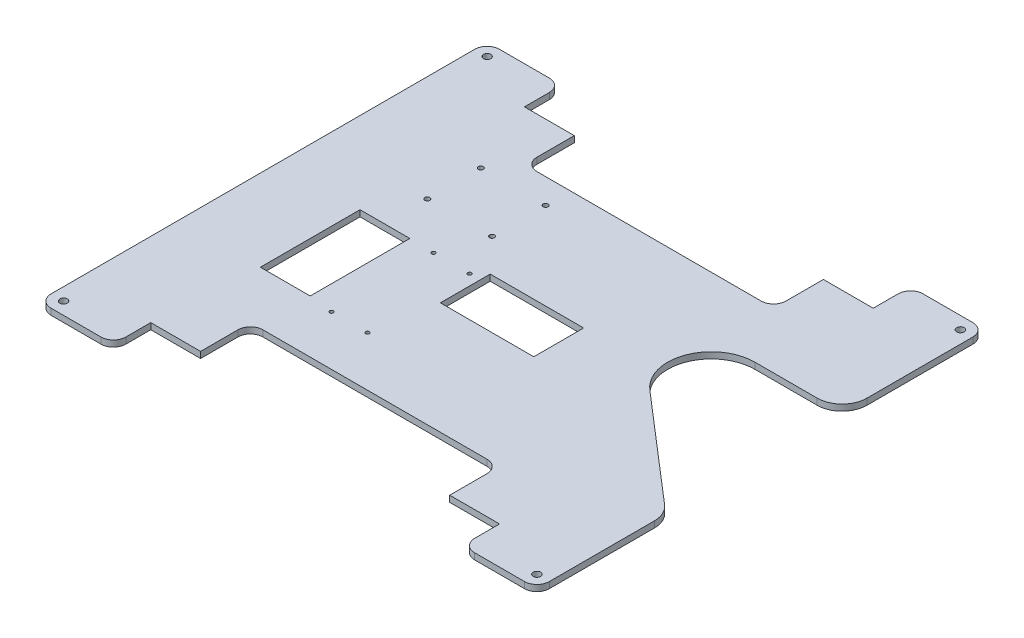
SolidWorks part; units mm, degrees
ref_plane "前基準面" through (0, 0, 0) normal (0, 0, 1) x (1, 0, 0)
ref_plane "上基準面" through (0, 0, 0) normal (0, 1, 0) x (1, 0, 0)
ref_plane "右基準面" through (0, 0, 0) normal (1, 0, 0) x (0, 0, -1)
sketch "草圖4" plane through (0, 0, 0) normal (0, 1, 0) x (1, 0, 0)
  line L0 (-200, 180) -> (-140, 180)
  line L1 (-140, 180) -> (-140, 150)
  line L2 (-140, 150) -> (-100, 150)
  line L3 (-100, 150) -> (-100, 110)
  line L4 (-100, 110) -> (100, 110)
  line L5 (100, 110) -> (100, 150)
  line L6 (100, 150) -> (140, 150)
  line L7 (140, 150) -> (140, 180)
  line L8 (140, 180) -> (200, 180)
  line L9 (-200, 180) -> (-200, -180)
  line L10 (-200, -180) -> (-140, -180)
  line L11 (-140, -180) -> (-140, -150)
  line L12 (-140, -150) -> (-100, -150)
  line L13 (-100, -150) -> (-100, -110)
  line L14 (-100, -110) -> (100, -110)
  line L15 (100, -110) -> (100, -150)
  line L16 (100, -150) -> (140, -150)
  line L17 (140, -150) -> (140, -180)
  line L18 (140, -180) -> (200, -180)
  line L19 (200, -180) -> (200, 180)
  line L20 (-100, 150) -> (100, 150) construction
  line L22 (100, -150) -> (-100, -150) construction
  line L24 (-140, 180) -> (140, 180) construction
  line L25 (140, -180) -> (-140, -180) construction
  line L27 (-100, 110) -> (100, -110) construction
  circle A0 centre (0, 0) radius 15
  dimension "D9" = 30
  dimension "D1" = 40
  dimension "D2" = 60
  dimension "D3" = 200
  dimension "D4" = 30
  dimension "D5" = 70
  dimension "D6" = 360
  dimension "D7" = 60
  dimension "D8" = 40
extrude "伸長1" add sketch "草圖4" along normal blind 5
sketch "草圖6" plane through (0, 5, 0) normal (0, 1, 0) x (-1, 0, 0)
  line L0 (200, -180) -> (200, 180) construction
  line L1 (115, -90) -> (63, -90) construction
  line L2 (115, -90) -> (115, -47) construction
  line L3 (115, -47) -> (63, -47) construction
  line L4 (63, -90) -> (63, -47) construction
  line L5 (115, -90) -> (63, -47) construction
  line L6 (115, -47) -> (63, -90) construction
  line L7 (75, -12) -> (46, -12) construction
  line L8 (75, -12) -> (75, 70) construction
  line L9 (75, 70) -> (46, 70) construction
  line L10 (46, -12) -> (46, 70) construction
  line L11 (75, -12) -> (46, 70) construction
  line L12 (75, 70) -> (46, -12) construction
  line L13 (33, -16.5) -> (-33, -16.5) construction
  line L14 (33, -16.5) -> (33, 16.5) construction
  line L15 (33, 16.5) -> (-33, 16.5) construction
  line L16 (-33, -16.5) -> (-33, 16.5) construction
  line L17 (33, -16.5) -> (-33, 16.5) construction
  line L18 (33, 16.5) -> (-33, -16.5) construction
  line L19 (130, -10) -> (99, -10) construction
  line L20 (130, -10) -> (130, 65) construction
  line L21 (130, 65) -> (99, 65) construction
  line L22 (99, -10) -> (99, 65) construction
  line L23 (130, -10) -> (99, 65) construction
  line L24 (130, 65) -> (99, -10) construction
  line L25 (100, 110) -> (-100, 110) construction
  line L26 (-100, -110) -> (100, -110) construction
  circle A0 centre (75, -12) radius 1.5
  circle A1 centre (46, -12) radius 1.5
  circle A2 centre (46, 70) radius 1.5
  circle A3 centre (75, 70) radius 1.5
  circle A4 centre (63, -90) radius 2
  circle A5 centre (115, -90) radius 2
  circle A6 centre (115, -47) radius 2
  circle A7 centre (63, -47) radius 2
  circle A8 centre (130, -10) radius 1.6
  circle A9 centre (130, 65) radius 1.6
  circle A10 centre (99, 65) radius 1.6
  circle A11 centre (99, -10) radius 1.6
  circle A12 centre (33, 16.5) radius 1.75
  circle A13 centre (33, -16.5) radius 1.75
  circle A14 centre (-33, -16.5) radius 1.75
  circle A15 centre (-33, 16.5) radius 1.75
  point P0 (89, -68.5)
  point P5 (60.5, 29)
  point P10 (0, 0)
  point P15 (114.5, 27.5)
  dimension "D1" = 29
  dimension "D3" = 3
  dimension "D4" = 4
  dimension "D7" = 3.2
  dimension "D10" = 3.5
  dimension "D2" = 82
  dimension "D5" = 52
  dimension "D6" = 43
  dimension "D8" = 31
  dimension "D9" = 75
  dimension "D11" = 66
  dimension "D12" = 33
  dimension "D13" = 70
  dimension "D14" = 125
  dimension "D15" = 85
  dimension "D16" = 45
  dimension "D17" = 40
  dimension "D18" = 20
extrude "伸長2" cut sketch "草圖6" against normal blind 5
sketch "草圖7" plane through (0, 5, 0) normal (0, 1, 0) x (1, 0, 0)
  line L0 (15, -92) -> (-15, -92) construction
  line L1 (15, -102) -> (-15, -102) construction
  line L2 (15, -102) -> (15, -52) construction
  line L3 (15, -52) -> (-15, -52) construction
  line L4 (-15, -102) -> (-15, -52) construction
  line L5 (15, -102) -> (-15, -52) construction
  line L6 (15, -52) -> (-15, -102) construction
  line L7 (-15, -82) -> (15, -82) construction
  line L8 (15, -72) -> (-15, -72) construction
  line L9 (-15, -62) -> (15, -62) construction
  line L10 (15, 62) -> (-15, 62) construction
  line L11 (15, 52) -> (-15, 52) construction
  line L12 (15, 52) -> (15, 102) construction
  line L13 (15, 102) -> (-15, 102) construction
  line L14 (-15, 52) -> (-15, 102) construction
  line L15 (15, 52) -> (-15, 102) construction
  line L16 (15, 102) -> (-15, 52) construction
  line L17 (-15, 72) -> (15, 72) construction
  line L18 (15, 82) -> (-15, 82) construction
  line L19 (-15, 92) -> (15, 92) construction
  line L20 (0, 77) -> (0, -77) construction
  line L21 (-100, -110) -> (100, -110) construction
  circle A0 centre (-15, -102) radius 1.5
  circle A1 centre (-15, -92) radius 1.5
  circle A2 centre (-15, -82) radius 1.5
  circle A3 centre (-15, -72) radius 1.5
  circle A4 centre (-15, -62) radius 1.5
  circle A5 centre (-15, -52) radius 1.5
  circle A6 centre (15, -102) radius 1.5
  circle A7 centre (15, -92) radius 1.5
  circle A8 centre (15, -72) radius 1.5
  circle A9 centre (15, -62) radius 1.5
  circle A10 centre (15, -52) radius 1.5
  circle A11 centre (15, -82) radius 1.5
  circle A12 centre (-15, 52) radius 1.5
  circle A13 centre (-15, 62) radius 1.5
  circle A14 centre (-15, 72) radius 1.5
  circle A15 centre (-15, 82) radius 1.5
  circle A16 centre (-15, 92) radius 1.5
  circle A17 centre (-15, 102) radius 1.5
  circle A18 centre (15, 52) radius 1.5
  circle A19 centre (15, 62) radius 1.5
  circle A20 centre (15, 82) radius 1.5
  circle A21 centre (15, 92) radius 1.5
  circle A22 centre (15, 102) radius 1.5
  circle A23 centre (15, 72) radius 1.5
  point P0 (0, -77)
  point P25 (37.8027, -51.0899)
  point P26 (0, 77)
  dimension "D13" = 3
  dimension "D14" = 3
  dimension "D1" = 10
  dimension "D2" = 10
  dimension "D3" = 10
  dimension "D4" = 10
  dimension "D5" = 10
  dimension "D6" = 30
  dimension "D7" = 50
  dimension "D8" = 30
  dimension "D9" = 10
  dimension "D10" = 10
  dimension "D11" = 10
  dimension "D12" = 10
  dimension "D15" = 8
extrude "伸長3" [suppressed] cut sketch "草圖7" against normal through all
sketch "草圖8" plane through (0, 5, 0) normal (0, 1, 0) x (1, 0, 0)
  line L0 (-140, 180) -> (-200, 180) construction
  line L1 (190, 170) -> (-190, 170) construction
  line L2 (190, 170) -> (190, -170) construction
  line L3 (190, -170) -> (-190, -170) construction
  line L4 (-190, 170) -> (-190, -170) construction
  line L5 (190, 170) -> (-190, -170) construction
  line L6 (190, -170) -> (-190, 170) construction
  line L7 (-200, 180) -> (-200, -180) construction
  circle A0 centre (190, 170) radius 3
  circle A1 centre (-190, 170) radius 3
  circle A2 centre (-190, -170) radius 3
  circle A3 centre (190, -170) radius 3
  point P8 (0, 0)
  dimension "D1" = 6
  dimension "D2" = 10
  dimension "D3" = 10
extrude "伸長4" cut sketch "草圖8" against normal blind 10
sketch "草圖10" plane through (0, 5, 0) normal (0, 1, 0) x (1, 0, 0)
  line L0 (50, 50) -> (95, 50) construction
  line L1 (100, -50) -> (95, -50)
  line L2 (100, -50) -> (100, -25)
  line L3 (100, -25) -> (95, -25)
  line L4 (95, -50) -> (95, -25)
  line L5 (50, -50) -> (45, -50)
  line L6 (50, -50) -> (50, -25)
  line L7 (50, -25) -> (45, -25)
  line L8 (45, -50) -> (45, -25)
  line L9 (100, 25) -> (95, 25)
  line L10 (100, 25) -> (100, 50)
  line L11 (100, 50) -> (95, 50)
  line L12 (95, 25) -> (95, 50)
  line L13 (50, 25) -> (45, 25)
  line L14 (50, 25) -> (50, 50)
  line L15 (50, 50) -> (45, 50)
  line L16 (45, 25) -> (45, 50)
  line L17 (50, -25) -> (95, -25) construction
  line L18 (45, 25) -> (45, -25) construction
  line L19 (95, 25) -> (95, -25) construction
  line L20 (50, 25) -> (95, 25) construction
  line L21 (50, -50) -> (95, -50) construction
  line L22 (50, 25) -> (50, -25) construction
  line L23 (100, 25) -> (100, -25) construction
  line L24 (50, 12.5) -> (95, 12.5) construction
  line L25 (45, 12.5) -> (50, 12.5)
  line L26 (45, 12.5) -> (45, -12.5)
  line L27 (45, -12.5) -> (50, -12.5)
  line L28 (50, 12.5) -> (50, -12.5)
  line L29 (95, 12.5) -> (100, 12.5)
  line L30 (95, 12.5) -> (95, -12.5)
  line L31 (95, -12.5) -> (100, -12.5)
  line L32 (100, 12.5) -> (100, -12.5)
  line L33 (50, -12.5) -> (95, -12.5) construction
  line L34 (50, 12.5) -> (95, -12.5) construction
  line L35 (50, -12.5) -> (95, 12.5) construction
  line L36 (72.5, 0) -> (0, 0) construction
  dimension "D1" = 25
  dimension "D2" = 5
  dimension "D3" = 45
  dimension "D4" = 100
  dimension "D5" = 12.5
  dimension "D6" = 45
extrude "伸長6" [suppressed] cut sketch "草圖10" against normal blind 10
sketch "草圖12" plane through (0, 5, 0) normal (0, 1, 0) x (1, 0, 0)
  line L0 (135, 94.9) -> (135, 85.1) construction
  line L1 (139.5, 100) -> (180, 100)
  line L2 (139.5, 100) -> (139.5, 80)
  line L3 (139.5, 80) -> (180, 80)
  line L4 (180, 100) -> (180, 80)
  line L5 (139.5, 100) -> (180, 80) construction
  line L6 (139.5, 80) -> (180, 100) construction
  line L7 (184.5, 94.9) -> (184.5, 85.1) construction
  line L8 (135, 90) -> (184.5, 90) construction
  line L9 (135, 94.9) -> (184.5, 94.9) construction
  line L10 (135, -85.1) -> (135, -94.9) construction
  line L11 (139.5, -80) -> (180, -80)
  line L12 (139.5, -80) -> (139.5, -100)
  line L13 (139.5, -100) -> (180, -100)
  line L14 (180, -80) -> (180, -100)
  line L15 (139.5, -80) -> (180, -100) construction
  line L16 (139.5, -100) -> (180, -80) construction
  line L17 (184.5, -85.1) -> (184.5, -94.9) construction
  line L18 (135, -90) -> (184.5, -90) construction
  line L19 (135, -85.1) -> (184.5, -85.1) construction
  line L20 (159.75, 90) -> (159.75, -90) construction
  line L21 (0, 0) -> (159.75, 0) construction
  line L22 (200, -180) -> (200, 180) construction
  line L23 (200, 180) -> (140, 180) construction
  circle A0 centre (135, 94.9) radius 2.25
  circle A1 centre (135, 85.1) radius 2.25
  circle A2 centre (184.5, 94.9) radius 2.25
  circle A3 centre (184.5, 85.1) radius 2.25
  circle A4 centre (135, -85.1) radius 2.25
  circle A5 centre (135, -94.9) radius 2.25
  circle A6 centre (184.5, -85.1) radius 2.25
  circle A7 centre (184.5, -94.9) radius 2.25
  point P0 (159.75, 90)
  point P15 (159.75, -90)
  dimension "D1" = 4.5
  dimension "D6" = 4.5
  dimension "D2" = 40.5
  dimension "D3" = 20
  dimension "D4" = 9.8
  dimension "D5" = 4.5
  dimension "D7" = 40.5
  dimension "D8" = 20
  dimension "D9" = 9.8
  dimension "D10" = 4.5
  dimension "D11" = 20
  dimension "D12" = 80
extrude "伸長7" [suppressed] cut sketch "草圖12" against normal blind 10
sketch "草圖13" plane through (0, 5, 0) normal (0, 1, 0) x (-1, 0, 0)
  line L0 (-152.5, -138.75) -> (-180, -138.75) construction
  line L1 (180, -138.75) -> (152.5, -138.75) construction
  line L2 (180, -138.75) -> (180, -111.25) construction
  line L3 (180, -111.25) -> (152.5, -111.25) construction
  line L4 (152.5, -138.75) -> (152.5, -111.25) construction
  line L5 (180, -138.75) -> (152.5, -111.25) construction
  line L6 (180, -111.25) -> (152.5, -138.75) construction
  line L7 (-152.5, -138.75) -> (-152.5, -111.25) construction
  line L8 (-152.5, -111.25) -> (-180, -111.25) construction
  line L9 (-180, -138.75) -> (-180, -111.25) construction
  line L10 (-152.5, -138.75) -> (-180, -111.25) construction
  line L11 (-152.5, -111.25) -> (-180, -138.75) construction
  line L12 (180, 111.25) -> (152.5, 111.25) construction
  line L13 (180, 111.25) -> (180, 138.75) construction
  line L14 (180, 138.75) -> (152.5, 138.75) construction
  line L15 (152.5, 111.25) -> (152.5, 138.75) construction
  line L16 (180, 111.25) -> (152.5, 138.75) construction
  line L17 (180, 138.75) -> (152.5, 111.25) construction
  line L18 (-152.5, 111.25) -> (-180, 111.25) construction
  line L19 (-152.5, 111.25) -> (-152.5, 138.75) construction
  line L20 (-152.5, 138.75) -> (-180, 138.75) construction
  line L21 (-180, 111.25) -> (-180, 138.75) construction
  line L22 (-152.5, 111.25) -> (-180, 138.75) construction
  line L23 (-152.5, 138.75) -> (-180, 111.25) construction
  line L24 (-200, 180) -> (-200, -180) construction
  line L25 (166.25, -125) -> (-166.25, -125) construction
  line L26 (166.25, -125) -> (166.25, 125) construction
  line L27 (166.25, 125) -> (-166.25, 125) construction
  line L28 (-166.25, -125) -> (-166.25, 125) construction
  line L29 (166.25, -125) -> (-166.25, 125) construction
  line L30 (166.25, 125) -> (-166.25, -125) construction
  line L31 (100, -150) -> (140, -150) construction
  circle A0 centre (180, -138.75) radius 2.5
  circle A1 centre (152.5, -138.75) radius 2.5
  circle A2 centre (152.5, -111.25) radius 2.5
  circle A3 centre (180, -111.25) radius 2.5
  circle A4 centre (-152.5, -138.75) radius 2.5
  circle A5 centre (-180, -138.75) radius 2.5
  circle A6 centre (-180, -111.25) radius 2.5
  circle A7 centre (-152.5, -111.25) radius 2.5
  circle A8 centre (180, 111.25) radius 2.5
  circle A9 centre (152.5, 111.25) radius 2.5
  circle A10 centre (152.5, 138.75) radius 2.5
  circle A11 centre (180, 138.75) radius 2.5
  circle A12 centre (-152.5, 111.25) radius 2.5
  circle A13 centre (-180, 111.25) radius 2.5
  circle A14 centre (-180, 138.75) radius 2.5
  circle A15 centre (-152.5, 138.75) radius 2.5
  point P0 (166.25, -125)
  point P9 (-166.25, -125)
  point P18 (166.25, 125)
  point P27 (-166.25, 125)
  point P36 (0, 0)
  dimension "D1" = 5
  dimension "D2" = 27.5
  dimension "D3" = 27.5
  dimension "D4" = 27.5
  dimension "D5" = 27.5
  dimension "D6" = 27.5
  dimension "D7" = 27.5
  dimension "D8" = 27.5
  dimension "D9" = 27.5
  dimension "D10" = 20
  dimension "D11" = 25
extrude "伸長8" [suppressed] cut sketch "草圖13" against normal blind 10
sketch "草圖14" plane through (0, 5, 0) normal (0, 1, 0) x (1, 0, 0)
  line L0 (200, 0) -> (280, 0) construction
  line L1 (200, -180) -> (200, 180) construction
  circle A0 centre (280, 0) radius 100
  dimension "D1" = 200
  dimension "D2" = 80
extrude "伸長9" [suppressed] cut sketch "草圖14" against normal blind 10
sketch "草圖15" plane through (0, 5, 0) normal (0, 1, 0) x (1, 0, 0)
  line L0 (155, 5) -> (165, 5) construction
  line L1 (115, 5) -> (125, 5) construction
  line L2 (115, 5) -> (115, -5) construction
  line L3 (115, -5) -> (125, -5) construction
  line L4 (125, 5) -> (125, -5) construction
  line L5 (115, 5) -> (125, -5) construction
  line L6 (115, -5) -> (125, 5) construction
  line L7 (155, 5) -> (155, -5) construction
  line L8 (155, -5) -> (165, -5) construction
  line L9 (165, 5) -> (165, -5) construction
  line L10 (155, 5) -> (165, -5) construction
  line L11 (155, -5) -> (165, 5) construction
  line L12 (135, 5) -> (145, 5) construction
  line L13 (135, 5) -> (135, -5) construction
  line L14 (135, -5) -> (145, -5) construction
  line L15 (145, 5) -> (145, -5) construction
  line L16 (135, 5) -> (145, -5) construction
  line L17 (135, -5) -> (145, 5) construction
  line L18 (120, 0) -> (140, 0) construction
  line L19 (140, 0) -> (160, 0) construction
  line L20 (120, 0) -> (0, 0) construction
  circle A0 centre (125, 5) radius 1.5
  circle A1 centre (125, -5) radius 1.5
  circle A2 centre (115, 5) radius 1.5
  circle A3 centre (115, -5) radius 1.5
  circle A4 centre (165, 5) radius 1.5
  circle A5 centre (165, -5) radius 1.5
  circle A6 centre (155, 5) radius 1.5
  circle A7 centre (155, -5) radius 1.5
  circle A8 centre (145, 5) radius 1.5
  circle A9 centre (145, -5) radius 1.5
  circle A10 centre (135, 5) radius 1.5
  circle A11 centre (135, -5) radius 1.5
  point P0 (120, 0)
  point P9 (128.8119, 3.5381)
  point P10 (160, 0)
  point P19 (202.378, -1.6151)
  point P20 (140, 0)
  point P29 (344.3803, 3.9326)
  dimension "D1" = 3
  dimension "D4" = 3
  dimension "D7" = 3
  dimension "D2" = 10
  dimension "D3" = 10
  dimension "D5" = 10
  dimension "D6" = 10
  dimension "D8" = 10
  dimension "D9" = 10
  dimension "D10" = 10
  dimension "D11" = 10
  dimension "D12" = 120
extrude "伸長10" [suppressed] cut sketch "草圖15" against normal blind 10
sketch "草圖17" plane through (0, 5, 0) normal (0, 1, 0) x (-1, 0, 0)
  line L0 (-108, -134) -> (-133.89, -134) construction
  line L1 (-140, -150) -> (-100, -150) construction
  line L2 (-100, -150) -> (-100, -110) construction
  line L3 (-108, 134) -> (-133.89, 134) construction
  line L4 (133.89, -134) -> (108, -134) construction
  line L5 (133.89, 134) -> (108, 134) construction
  line L6 (133.89, -134) -> (133.89, 134) construction
  line L7 (133.89, 134) -> (-108, 134) construction
  line L8 (-108, 134) -> (-108, -134) construction
  line L9 (-108, -134) -> (133.89, -134) construction
  line L10 (100, -110) -> (100, -150) construction
  line L11 (140, 150) -> (100, 150) construction
  circle A0 centre (-108, -134) radius 1.5
  circle A1 centre (-133.89, -134) radius 1.5
  circle A2 centre (-108, 134) radius 1.5
  circle A3 centre (-133.89, 134) radius 1.5
  circle A4 centre (133.89, -134) radius 1.5
  circle A5 centre (108, -134) radius 1.5
  circle A6 centre (133.89, 134) radius 1.5
  circle A7 centre (108, 134) radius 1.5
  dimension "D1" = 3
  dimension "D8" = 3
  dimension "D9" = 3
  dimension "D10" = 3
  dimension "D2" = 25.89
  dimension "D3" = 16
  dimension "D4" = 8
  dimension "D5" = 25.89
  dimension "D6" = 25.89
  dimension "D7" = 25.89
  dimension "D11" = 8
  dimension "D12" = 16
extrude "伸長11" [suppressed] cut sketch "草圖17" against normal blind 10
sketch "草圖18" plane through (0, 5, 0) normal (0, 1, 0) x (-1, 0, 0)
  line L0 (160, -70) -> (176, -70) construction
  line L1 (163, -70) -> (160, -70)
  line L2 (163, -70) -> (163, -60)
  line L3 (163, -60) -> (160, -60)
  line L4 (160, -70) -> (160, -60)
  line L5 (176, -70) -> (173, -70)
  line L6 (176, -70) -> (176, -60)
  line L7 (176, -60) -> (173, -60)
  line L8 (173, -70) -> (173, -60)
  line L9 (176, -60) -> (160, -60) construction
  line L10 (160, -5) -> (176, -5) construction
  line L11 (163, -5) -> (160, -5)
  line L12 (163, -5) -> (163, 5)
  line L13 (163, 5) -> (160, 5)
  line L14 (160, -5) -> (160, 5)
  line L15 (176, -5) -> (173, -5)
  line L16 (176, -5) -> (176, 5)
  line L17 (176, 5) -> (173, 5)
  line L18 (173, -5) -> (173, 5)
  line L19 (176, 5) -> (160, 5) construction
  line L20 (160, 60) -> (176, 60) construction
  line L21 (163, 60) -> (160, 60)
  line L22 (163, 60) -> (163, 70)
  line L23 (163, 70) -> (160, 70)
  line L24 (160, 60) -> (160, 70)
  line L25 (176, 60) -> (173, 60)
  line L26 (176, 60) -> (176, 70)
  line L27 (176, 70) -> (173, 70)
  line L28 (173, 60) -> (173, 70)
  line L29 (176, 70) -> (160, 70) construction
  line L30 (40, -43) -> (40, -33) construction
  line L31 (40, -46) -> (30, -46)
  line L32 (40, -46) -> (40, -43)
  line L33 (40, -43) -> (30, -43)
  line L34 (30, -46) -> (30, -43)
  line L35 (40, -33) -> (30, -33)
  line L36 (40, -33) -> (40, -30)
  line L37 (40, -30) -> (30, -30)
  line L38 (30, -33) -> (30, -30)
  line L39 (100, 83) -> (100, 93) construction
  line L40 (30, -43) -> (30, -33) construction
  line L41 (100, 80) -> (90, 80)
  line L42 (100, 80) -> (100, 83)
  line L43 (100, 83) -> (90, 83)
  line L44 (90, 80) -> (90, 83)
  line L45 (100, 93) -> (90, 93)
  line L46 (100, 93) -> (100, 96)
  line L47 (100, 96) -> (90, 96)
  line L48 (90, 93) -> (90, 96)
  line L49 (90, 83) -> (90, 93) construction
  line L50 (140, -43) -> (140, -33) construction
  line L51 (140, -46) -> (130, -46)
  line L52 (140, -46) -> (140, -43)
  line L53 (140, -43) -> (130, -43)
  line L54 (130, -46) -> (130, -43)
  line L55 (140, -33) -> (130, -33)
  line L56 (140, -33) -> (140, -30)
  line L57 (140, -30) -> (130, -30)
  line L58 (130, -33) -> (130, -30)
  line L59 (130, -43) -> (130, -33) construction
  line L60 (176, -60) -> (176, -5) construction
  line L61 (176, 60) -> (176, 5) construction
  line L62 (130, -46) -> (40, -46) construction
  line L63 (160, 0) -> (0, 0) construction
  line L64 (200, -180) -> (200, 180) construction
  dimension "D1" = 3
  dimension "D2" = 10
  dimension "D3" = 10
  dimension "D4" = 3
  dimension "D5" = 10
  dimension "D6" = 3
  dimension "D7" = 10
  dimension "D8" = 3
  dimension "D9" = 3
  dimension "D10" = 10
  dimension "D11" = 10
  dimension "D12" = 10
  dimension "D13" = 10
  dimension "D14" = 3
  dimension "D15" = 3
  dimension "D16" = 10
  dimension "D17" = 10
  dimension "D18" = 3
  dimension "D19" = 3
  dimension "D20" = 10
  dimension "D21" = 10
  dimension "D22" = 55
  dimension "D23" = 160
  dimension "D24" = 90
  dimension "D25" = 30
  dimension "D26" = 30
  dimension "D27" = 110
  dimension "D28" = 100
extrude "伸長12" [suppressed] cut sketch "草圖18" against normal blind 10
fillet "圓角1" radius 10 12 edges at (200, 2.5, 180) (-100, 2.5, 110) (100, 2.5, 110) (140, 2.5, 180) (-140, 2.5, 180) (-200, 2.5, 180) (-200, 2.5, -180) (-140, 2.5, -180) (-100, 2.5, -110) (100, 2.5, -110) (140, 2.5, -180) (200, 2.5, -180)
sketch "草圖21" plane through (0, 5, 0) normal (0, 1, 0) x (1, 0, 0)
  line L0 (200, 65) -> (130, 65)
  line L1 (200, -170) -> (200, 170) construction
  line L2 (140, 150) -> (100, 150) construction
  line L3 (130, 65) -> (130, -5) construction
  line L4 (107.1537, 3.485) -> (200, -76.515)
  line L5 (200, -170) -> (200, 170) construction
  arc A0 (130, 65) -> (107.1537, 3.485) centre (130, 30) ccw
  dimension "D1" = 70
  dimension "D2" = 120
  dimension "D3" = 70
  dimension "D4" = 80
extrude "伸長24" cut sketch "草圖21" against normal through all and the other way through all
sketch "草圖22" plane through (0, 5, 0) normal (0, 1, 0) x (-1, 0, 0)
  line L0 (-130, -30) -> (-130, 120) construction
  line L1 (-125.1, 93.5) -> (-134.9, 93.5) construction
  line L2 (-119.5, 98.25) -> (-140.5, 98.25) construction
  line L3 (-119.5, 98.25) -> (-119.5, 138.75) construction
  line L4 (-119.5, 138.75) -> (-140.5, 138.75) construction
  line L5 (-140.5, 98.25) -> (-140.5, 138.75) construction
  line L6 (-119.5, 98.25) -> (-140.5, 138.75) construction
  line L7 (-119.5, 138.75) -> (-140.5, 98.25) construction
  line L8 (-134.9, 93.5) -> (-134.9, 143.5) construction
  line L9 (-134.9, 143.5) -> (-125.1, 143.5) construction
  line L10 (-125.1, 143.5) -> (-125.1, 93.5) construction
  line L11 (-130, 93.5) -> (-130, 118.5) construction
  line L12 (-119.5, 97) -> (-140.5, 97)
  line L13 (-119.5, 97) -> (-119.5, 140)
  line L14 (-119.5, 140) -> (-140.5, 140)
  line L15 (-140.5, 97) -> (-140.5, 140)
  line L16 (-119.5, 97) -> (-140.5, 140) construction
  line L17 (-119.5, 140) -> (-140.5, 97) construction
  line L18 (-200, -65) -> (-200, -170) construction
  line L19 (-108.5, -100) -> (-151.5, -100)
  line L20 (-108.5, -100) -> (-108.5, -79)
  line L21 (-108.5, -79) -> (-151.5, -79)
  line L22 (-151.5, -100) -> (-151.5, -79)
  line L23 (-108.5, -100) -> (-151.5, -79) construction
  line L24 (-108.5, -79) -> (-151.5, -100) construction
  line L25 (-105, -94.4) -> (-155, -94.4) construction
  line L26 (-105, -94.4) -> (-105, -84.6) construction
  line L27 (-105, -84.6) -> (-155, -84.6) construction
  line L28 (-155, -94.4) -> (-155, -84.6) construction
  line L29 (-105, -94.4) -> (-155, -84.6) construction
  line L30 (-105, -84.6) -> (-155, -94.4) construction
  line L31 (-140, -150) -> (-100, -150) construction
  circle A0 centre (-125.1, 93.5) radius 2.25
  circle A1 centre (-134.9, 93.5) radius 2.25
  circle A2 centre (-125.1, 143.5) radius 2.25
  circle A3 centre (-134.9, 143.5) radius 2.25
  circle A4 centre (-105, -94.4) radius 2.25
  circle A5 centre (-105, -84.6) radius 2.25
  circle A6 centre (-155, -94.4) radius 2.25
  circle A7 centre (-155, -84.6) radius 2.25
  point P3 (-130, 118.5)
  point P16 (-130, 118.5)
  point P23 (-130, -89.5)
  point P28 (-130, -89.5)
  dimension "D4" = 4.5
  dimension "D14" = 4.5
  dimension "D1" = 150
  dimension "D2" = 40.5
  dimension "D3" = 21
  dimension "D5" = 9.8
  dimension "D6" = 4.75
  dimension "D7" = 4.75
  dimension "D8" = 43
  dimension "D9" = 18.75
  dimension "D10" = 9.8
  dimension "D11" = 50
  dimension "D12" = 21
  dimension "D13" = 43
  dimension "D15" = 70
  dimension "D16" = 50
extrude "伸長25" [suppressed] cut sketch "草圖22" against normal blind 10
sketch "草圖23" plane through (0, 5, 0) normal (0, 1, 0) x (1, 0, 0)
  line L0 (-130, 10) -> (-99, -65) construction
  line L1 (-37.5, 20) -> (37.5, 20)
  line L2 (-37.5, 20) -> (-37.5, -20)
  line L3 (-37.5, -20) -> (37.5, -20)
  line L4 (37.5, 20) -> (37.5, -20)
  line L5 (-37.5, 20) -> (37.5, -20) construction
  line L6 (-37.5, -20) -> (37.5, 20) construction
  line L7 (-99, 10) -> (-130, 10) construction
  line L8 (-99, 10) -> (-99, -65) construction
  line L9 (-99, -65) -> (-130, -65) construction
  line L10 (-130, 10) -> (-130, -65) construction
  line L12 (-134.5, 12.5) -> (-94.5, 12.5)
  line L13 (-134.5, 12.5) -> (-134.5, -67.5)
  line L14 (-134.5, -67.5) -> (-94.5, -67.5)
  line L15 (-94.5, 12.5) -> (-94.5, -67.5)
  line L16 (-134.5, 12.5) -> (-94.5, -67.5) construction
  line L17 (-134.5, -67.5) -> (-94.5, 12.5) construction
  point P0 (0, 0)
  point P6 (-114.5, -27.5)
  dimension "D1" = 75
  dimension "D2" = 40
  dimension "D3" = 40
  dimension "D4" = 80
extrude "伸長26" cut sketch "草圖23" against normal through all
fillet "圓角2" radius 20 2 edges at (200, 2.5, 76.515) (200, 2.5, -65)
ref_plane "平面1" [suppressed] through (119.5, 5, 97) normal (-1, 0, 0) x (0, 0, 1)
